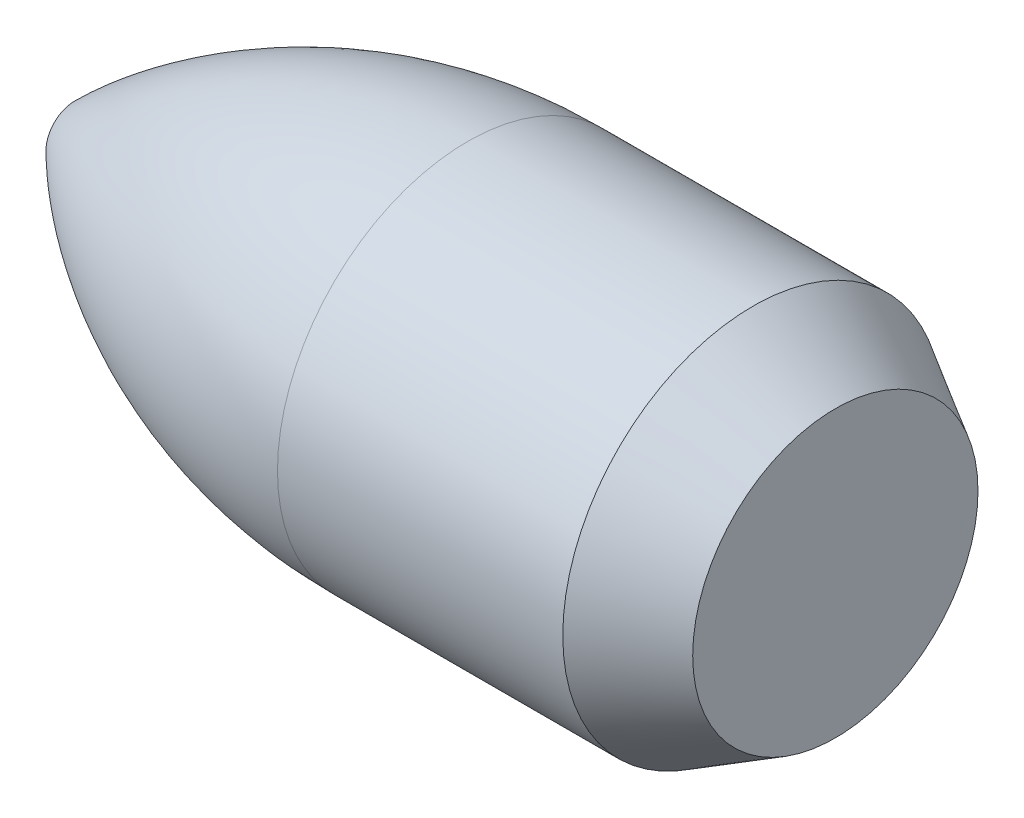
SolidWorks part; units mm, degrees
ref_plane "Спереди" through (0, 0, 0) normal (0, 0, 1) x (1, 0, 0)
ref_plane "Сверху" through (0, 0, 0) normal (0, 1, 0) x (1, 0, 0)
ref_plane "Справа" through (0, 0, 0) normal (1, 0, 0) x (0, 0, -1)
sketch "Эскиз1" plane through (0, 0, 0) normal (0, 0, 1) x (1, 0, 0)
  line L0 (0, 0) -> (0, 1.5)
  line L1 (20.6699, 10) -> (35.6699, 10)
  line L2 (35.6699, 10) -> (40, 7.5)
  line L3 (40, 7.5) -> (40, 0)
  line L4 (40, 0) -> (0, 0)
  line L5 (-8.0419, 0) -> (67.0118, 0) construction
  line L6 (29.3622, 10) -> (11.4394, 10) construction
  line L7 (9.3527, 10.8527) -> (-9.3527, -7.8527) construction
  spline S0 degree 3 poles (0, 1.5) (3.9489, 5.4489) (11.1421, 10) (20.6699, 10) knots 0 0 0 0 1 1 1 1
  point P11 (34.0832, 10)
  point P12 (19.5486, 10)
  point P13 (35.6684, 10)
  point P14 (36.9279, 10)
  point P15 (35.5004, 10)
  dimension "D1" = 20
  dimension "D7" = 45
  dimension "D2" = 40
  dimension "D3" = 3
  dimension "D4" = 30
  dimension "D5" = 15
  dimension "D6" = 15
revolve "Повернуть1" add sketch "Эскиз1" angle 360 about L5
